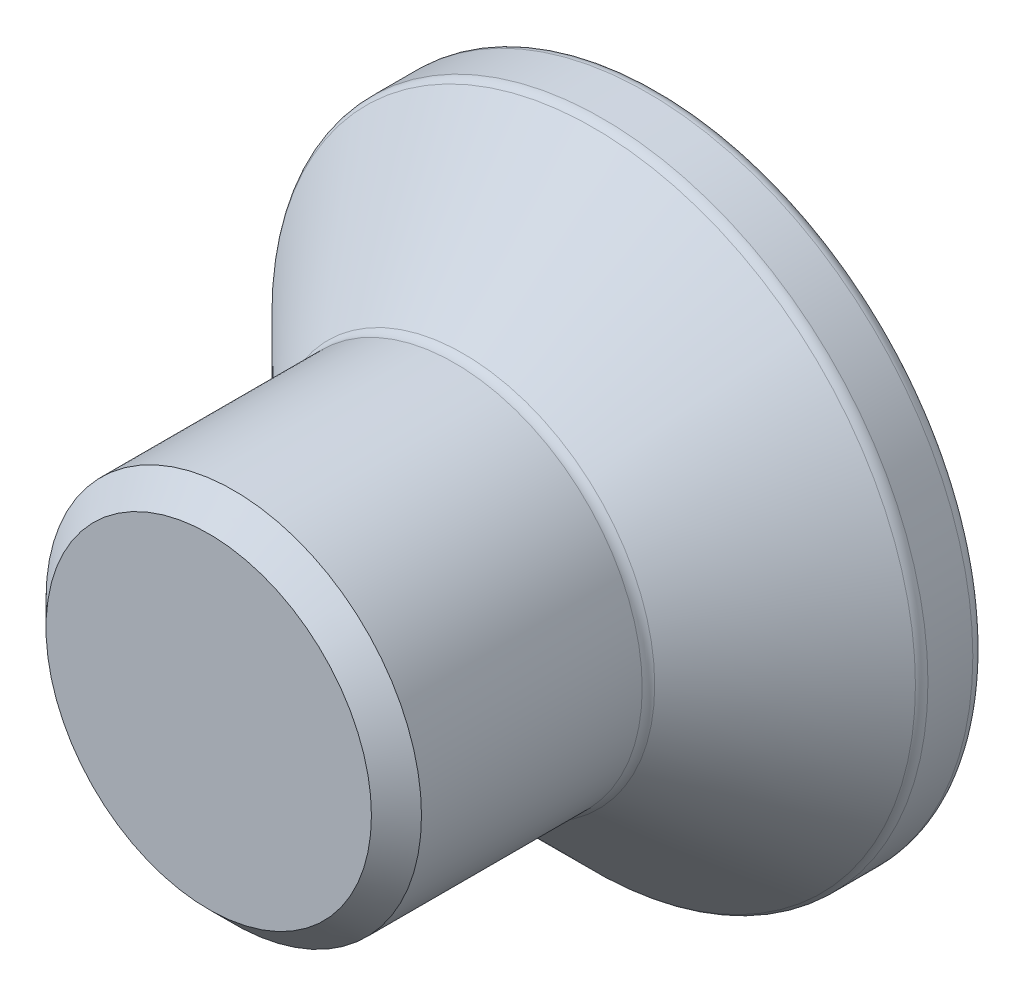
SolidWorks part; units mm, degrees
ref_plane "Front Plane" through (0, 0, 0) normal (0, 0, 1) x (1, 0, 0)
ref_plane "Top Plane" through (0, 0, 0) normal (0, 1, 0) x (1, 0, 0)
ref_plane "Right Plane" through (0, 0, 0) normal (1, 0, 0) x (0, 0, -1)
sketch "Sketch1" plane through (0, 0, 0) normal (0, 1, 0) x (1, 0, 0)
  line L0 (0, 0) -> (0, 7.0819) construction
  line L1 (0, 3.605) -> (2.6, 3.605)
  line L2 (2.6, 3.605) -> (2.6, 3.105)
  line L3 (2.6, 3.105) -> (1.5, 2.005)
  line L4 (1.5, 2.005) -> (1.5, 0)
  line L5 (1.5, 0) -> (0, 0)
  line L6 (0, 3.605) -> (0, 0)
  dimension "D1" = 2.6
  dimension "D2" = 45
  dimension "D3" = 1.5
  dimension "D4" = 0.5
revolve "Revolve1" add sketch "Sketch1" angle 360 about L0
sketch "Sketch2" plane through (0, 0, -3.605) normal (0, 0, -1) x (-1, 0, 0)
  line L1 (1.5, 0) -> (0.75, 1.299)
  line L2 (0.75, 1.299) -> (-0.75, 1.299)
  line L3 (-0.75, 1.299) -> (-1.5, 0)
  line L4 (-1.5, 0) -> (-0.75, -1.299)
  line L5 (-0.75, -1.299) -> (0.75, -1.299)
  line L6 (0.75, -1.299) -> (1.5, 0)
  circle A0 centre (0, 0) radius 1.299 construction
  dimension "D1" = 1.5
extrude "Cut-Extrude1" cut sketch "Sketch2" against normal blind 1
chamfer "Chamfer1" distance 0.5 angle 45 6 edges at (0, -1.299, -2.605) (1.125, -0.6495, -2.605) (1.125, 0.6495, -2.605) (0, 1.299, -2.605) (-1.125, 0.6495, -2.605) (-1.125, -0.6495, -2.605)
fillet "Fillet1" radius 0.1 3 edges at (1.5, 0, -2.005) (2.6, 0, -3.105) (2.6, 0, -3.605)
chamfer "Chamfer2" distance 0.2 angle 45 1 edges at (1.5, 0, 0)
